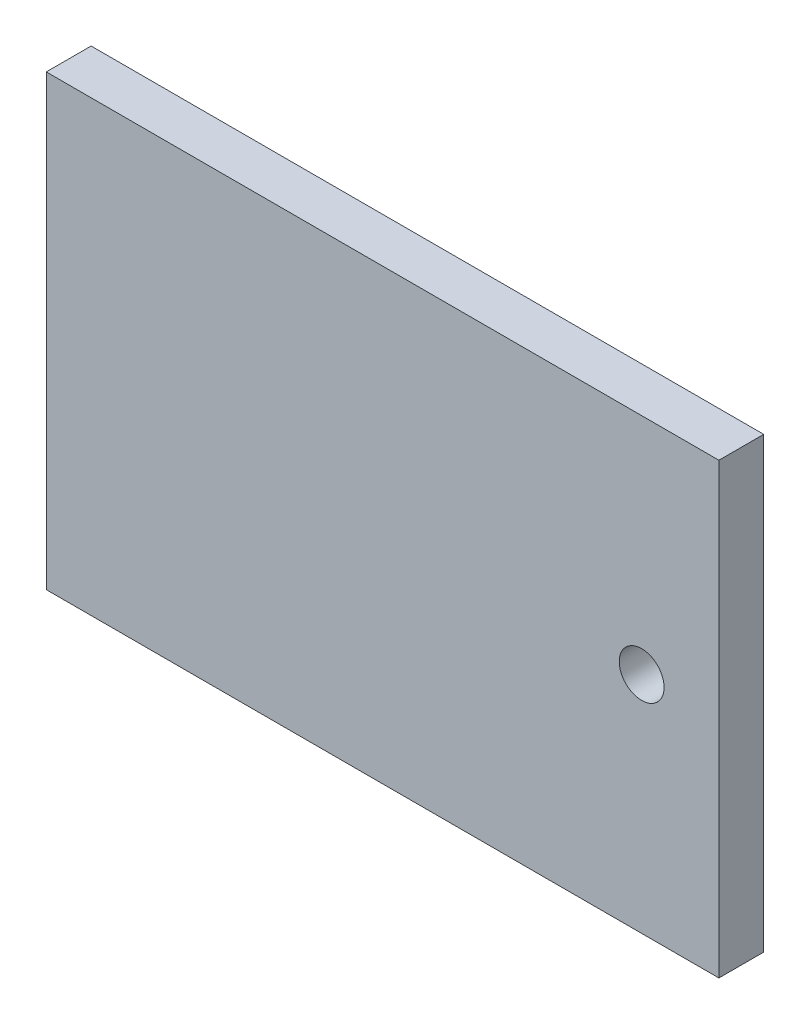
SolidWorks part; units mm, degrees
material "6061-T4 (SS)"
ref_plane "정면" through (0, 0, 0) normal (0, 0, 1) x (1, 0, 0)
ref_plane "윗면" through (0, 0, 0) normal (0, 1, 0) x (1, 0, 0)
ref_plane "우측면" through (0, 0, 0) normal (1, 0, 0) x (0, 0, -1)
sketch "스케치1" plane through (0, 0, 0) normal (0, 0, 1) x (1, 0, 0)
  line L1 (-15, 10) -> (15, 10)
  line L2 (-15, 10) -> (-15, -10)
  line L3 (-15, -10) -> (15, -10)
  line L4 (15, 10) -> (15, -10)
  line L5 (-15, 10) -> (15, -10) construction
  line L6 (-15, -10) -> (15, 10) construction
  point P0 (0, 0)
  dimension "D1" = 30
  dimension "D2" = 20
extrude "보스-돌출1" add sketch "스케치1" along normal blind 2
sketch "스케치2" plane through (0, 0, 2) normal (0, 0, 1) x (1, 0, 0)
  circle A0 centre (11.5553, 0) radius 1
  dimension "D1" = 2
extrude "컷-돌출1" cut sketch "스케치2" against normal blind 2
